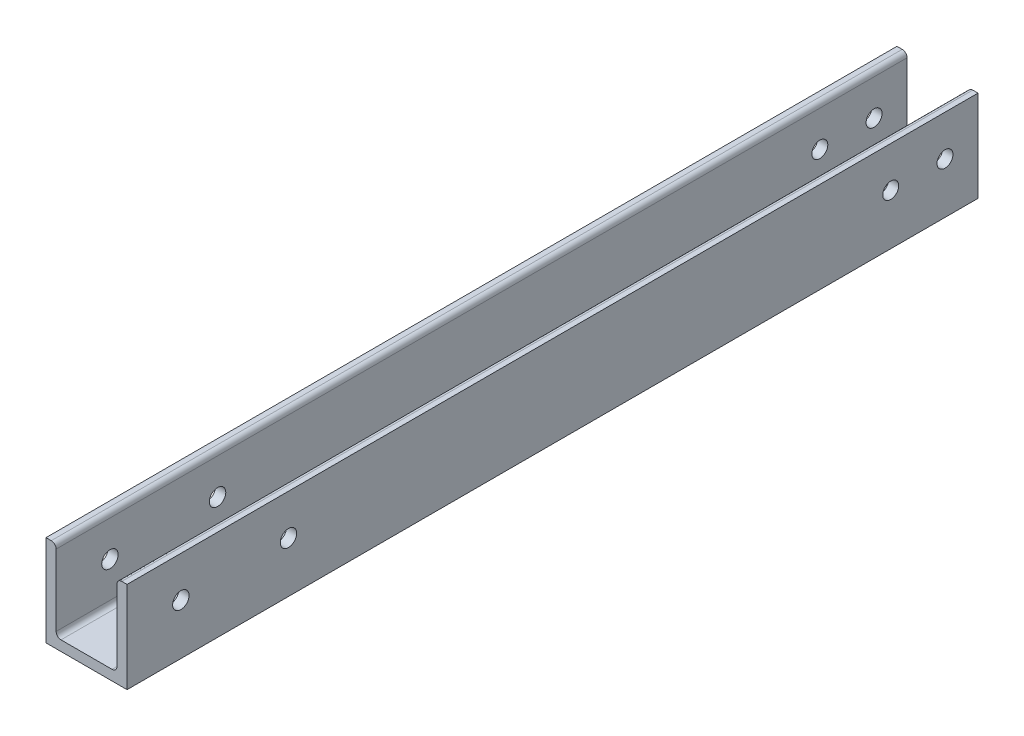
SolidWorks part; units mm, degrees
material "6061-T6 (SS)"
ref_plane "Front Plane" through (0, 0, 0) normal (0, 0, 1) x (1, 0, 0)
ref_plane "Top Plane" through (0, 0, 0) normal (0, 1, 0) x (1, 0, 0)
ref_plane "Right Plane" through (0, 0, 0) normal (1, 0, 0) x (0, 0, -1)
sketch "Sketch1" plane through (0, 0, 0) normal (0, 0, 1) x (1, 0, 0)
  line L1 (-12.7, 0) -> (12.7, 0)
  line L2 (-12.7, 0) -> (-12.7, 3.175)
  line L3 (-8.001, 3.175) -> (8.001, 3.175)
  line L4 (12.7, 0) -> (12.7, 6.35)
  line L6 (-12.7, 3.175) -> (-12.7, 28.575)
  line L7 (-12.7, 28.575) -> (-11.049, 28.575)
  line L8 (-9.525, 4.699) -> (-9.525, 27.051)
  line L10 (12.7, 6.35) -> (12.7, 28.575)
  line L11 (12.7, 28.575) -> (11.049, 28.575)
  line L12 (9.525, 4.699) -> (9.525, 27.051)
  arc A0 (11.049, 28.575) -> (9.525, 27.051) centre (11.049, 27.051) ccw
  arc A1 (-11.049, 28.575) -> (-9.525, 27.051) centre (-11.049, 27.051) cw
  arc A2 (-8.001, 3.175) -> (-9.525, 4.699) centre (-8.001, 4.699) cw
  arc A3 (8.001, 3.175) -> (9.525, 4.699) centre (8.001, 4.699) ccw
  point P10 (0, 0)
  point P14 (9.525, 28.575)
  point P17 (-9.525, 28.575)
  dimension "D6" = 1.524
  dimension "D1" = 25.4
  dimension "D2" = 3.175
  dimension "D3" = 3.175
  dimension "D4" = 3.175
  dimension "D5" = 25.4
extrude "Boss-Extrude1" add sketch "Sketch1" along normal blind 266.7
sketch "Sketch7" plane through (12.7, 0, 0) normal (1, 0, 0) x (0, 0, -1)
  line L0 (-266.7, 15.875) -> (-216.1087, 15.875) construction
  line L1 (-266.7, 0) -> (-266.7, 28.575) construction
  line L3 (-266.7, 28.575) -> (0, 28.575) construction
  circle A0 centre (-216.1087, 15.875) radius 2.575
  circle A1 centre (-249.8362, 15.875) radius 2.575
  dimension "D1" = 5.15
  dimension "D2" = 50.5913
  dimension "D3" = 16.8638
  dimension "D4" = 33.7275
  dimension "D5" = 12.7
extrude "Cut-Extrude5" cut sketch "Sketch7" against normal through all
sketch "Sketch8" plane through (-12.7, 0, 0) normal (-1, 0, 0) x (0, 0, 1)
  circle A0 centre (10.35, 15.875) radius 2.5 construction
  circle A1 centre (27.35, 15.875) radius 2.5 construction
  circle A3 centre (10.35, 15.875) radius 2.5
  circle A4 centre (27.35, 15.875) radius 2.5
extrude "Cut-Extrude7" cut sketch "Sketch8" against normal through all
